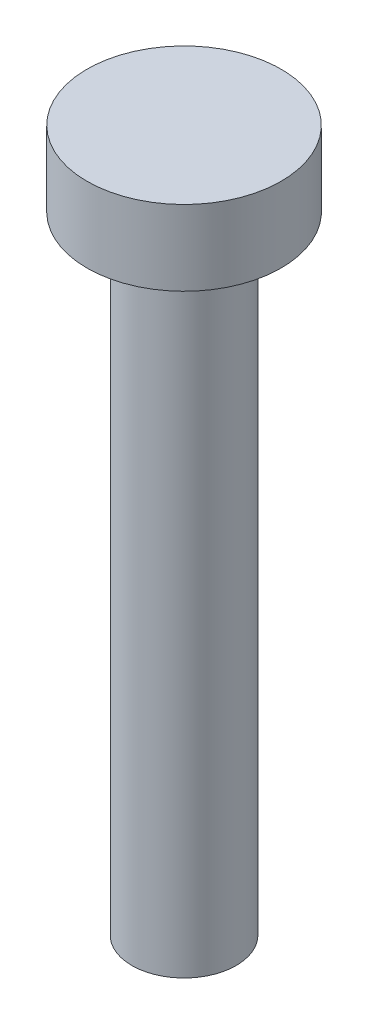
SolidWorks part; units mm, degrees
ref_plane "前视基准面" through (0, 0, 0) normal (0, 0, 1) x (1, 0, 0)
ref_plane "上视基准面" through (0, 0, 0) normal (0, 1, 0) x (1, 0, 0)
ref_plane "右视基准面" through (0, 0, 0) normal (1, 0, 0) x (0, 0, -1)
sketch "草图1" plane through (0, 0, 0) normal (0, 1, 0) x (1, 0, 0)
  circle A0 centre (0, 0) radius 2.5
  dimension "D1" = 5
extrude "凸台-拉伸1" add sketch "草图1" along normal blind 30
sketch "草图2" plane through (0, 30, 0) normal (0, 1, 0) x (1, 0, 0)
  circle A0 centre (0, 0) radius 4.65
  dimension "D1" = 9.3
extrude "凸台-拉伸2" add sketch "草图2" along normal blind 3.6
